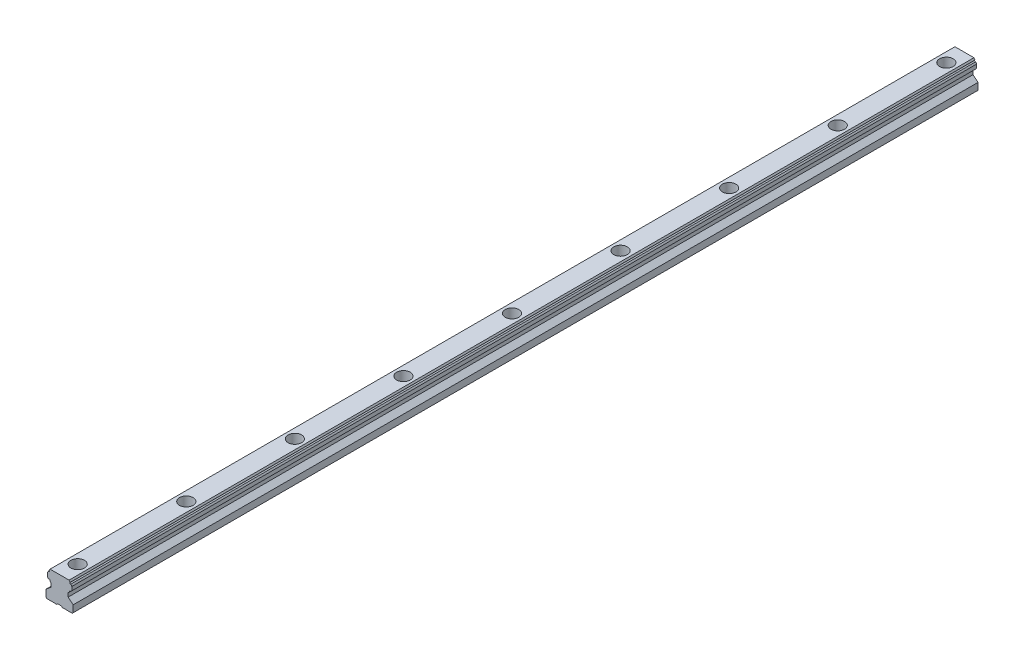
SolidWorks part; units mm, degrees
ref_plane "前视基准面" through (0, 0, 0) normal (0, 0, 1) x (1, 0, 0)
ref_plane "上视基准面" through (0, 0, 0) normal (0, 1, 0) x (1, 0, 0)
ref_plane "右视基准面" through (0, 0, 0) normal (1, 0, 0) x (0, 0, -1)
sketch "基准草图" plane through (0, 0, 0) normal (1, 0, 0) x (0, 0, -1)
  line L0 (0, 0) -> (60, 0) construction
  line L1 (0, 0) -> (0, 5)
  line L2 (60, 0) -> (80, 0) construction
  dimension "数量" = 5
  dimension "P" = 60
  dimension "E" = 20
sketch "草图1" plane through (0, 0, 0) normal (0, 0, 1) x (1, 0, 0)
  line L0 (0, 23.7) -> (0, 0) construction
  line L1 (-17, 21.7) -> (-17, 17.7)
  line L2 (17, 21.7) -> (17, 1)
  line L3 (-13, 23.7) -> (-13, 19.725) construction
  line L4 (-9.5, 23.7) -> (-9, 23.2)
  line L5 (-9, 23.2) -> (-3.3333, 23.2)
  line L6 (-3.3333, 23.2) -> (-2.8333, 23.7)
  line L7 (9.5, 23.7) -> (9, 23.2)
  line L8 (9, 23.2) -> (3.3333, 23.2)
  line L9 (3.3333, 23.2) -> (2.8333, 23.7)
  line L10 (-9.5, 23.7) -> (-15, 23.7)
  line L11 (15, 23.7) -> (9.5, 23.7)
  line L12 (-15, 23.7) -> (-17, 21.7)
  line L13 (2.8333, 23.7) -> (-2.8333, 23.7)
  line L14 (-16.2, 19.725) -> (16.2, 19.725)
  line L15 (-16.2, 19.725) -> (-16.5, 19.425)
  line L16 (-16.5, 19.425) -> (-16.5, 0.5)
  line L17 (-17, 17.7) -> (-16.5, 17.2) construction
  line L18 (-3.3333, 19.725) -> (-3.3333, 15.75)
  line L19 (3.3333, 19.725) -> (3.3333, 15.75)
  line L21 (-16, 0) -> (-7.5, 0)
  line L22 (-7.5, 0) -> (-4.75, 2.3075)
  line L23 (15, 23.7) -> (17, 21.7)
  line L24 (-4.75, 2.3075) -> (-4.75, 4.4182)
  line L25 (-4.75, 4.4182) -> (-5.4765, 5.0996)
  line L26 (-6.75, 6.294) -> (-6.75, 8.4047)
  line L27 (-6.75, 8.4047) -> (-6.2051, 9.2384)
  line L28 (-5.25, 10.7) -> (5.25, 10.7)
  line L29 (6.75, 8.4047) -> (6.2051, 9.2384)
  line L30 (6.75, 6.294) -> (6.75, 8.4047)
  line L31 (4.75, 4.4182) -> (5.4765, 5.0996)
  line L32 (4.75, 2.3075) -> (4.75, 4.4182)
  line L33 (7.5, 0) -> (4.75, 2.3075)
  line L34 (16, 0) -> (7.5, 0)
  line L35 (16.5, 19.425) -> (16.5, 0.5)
  line L36 (16.2, 19.725) -> (16.5, 19.425)
  line L37 (-7.5, 0) -> (-7.5, -3.8)
  line L38 (-7.5, -3.8) -> (-7, -4.3)
  line L39 (-7, -4.3) -> (-1.5, -4.3)
  line L40 (7.5, -3.8) -> (7, -4.3)
  line L41 (7.5, 0) -> (7.5, -3.8)
  line L42 (-1.5, -4.3) -> (-1, -3.8)
  line L43 (-1, -3.8) -> (1, -3.8)
  line L44 (1.5, -4.3) -> (1, -3.8)
  line L45 (1.5, -4.3) -> (7, -4.3)
  line L46 (-6.0235, 5.6126) -> (-6.75, 6.294)
  line L47 (-5.7949, 9.8662) -> (-5.25, 10.7)
  line L48 (5.7949, 9.8662) -> (5.25, 10.7)
  line L49 (6.0235, 5.6126) -> (6.75, 6.294)
  line L51 (8.2379, 3.1) -> (8.2379, 0.1) construction
  line L52 (6.7379, 1.6) -> (9.7379, 1.6) construction
  line L53 (8.0879, 2.9919) -> (8.0879, 1.75)
  line L54 (8.0879, 1.75) -> (6.846, 1.75)
  line L55 (8.3879, 1.75) -> (9.6299, 1.75)
  line L56 (8.3879, 2.9919) -> (8.3879, 1.75)
  line L57 (8.0879, 1.45) -> (6.846, 1.45)
  line L58 (8.3879, 1.45) -> (9.6299, 1.45)
  line L59 (8.3879, 0.2081) -> (8.3879, 1.45)
  line L60 (8.0879, 0.2081) -> (8.0879, 1.45)
  line L61 (-8.0879, 1.45) -> (-6.846, 1.45)
  line L62 (-8.0879, 0.2081) -> (-8.0879, 1.45)
  line L63 (-8.3879, 0.2081) -> (-8.3879, 1.45)
  line L64 (-8.3879, 1.45) -> (-9.6299, 1.45)
  line L65 (-8.3879, 1.75) -> (-9.6299, 1.75)
  line L66 (-8.0879, 1.75) -> (-6.846, 1.75)
  line L67 (-8.0879, 2.9919) -> (-8.0879, 1.75)
  line L68 (-8.3879, 2.9919) -> (-8.3879, 1.75)
  line L69 (-2.8333, 20.225) -> (2.8333, 20.225)
  line L70 (-3.3333, 19.725) -> (-2.8333, 20.225)
  line L71 (-16.75, 17.45) -> (-16.75, 0.75)
  line L72 (3.3333, 19.725) -> (2.8333, 20.225)
  line L73 (-16.75, 17.45) -> (-17, 17.7)
  line L74 (-16, 0) -> (-16.75, 0.75)
  line L75 (16, 0) -> (17, 1)
  arc A0 (-3.3333, 15.75) -> (3.3333, 15.75) centre (0, 15.75) ccw
  arc A1 (-6.2051, 9.2384) -> (-5.7949, 9.8662) centre (-6, 9.5523) ccw
  arc A2 (-5.4765, 5.0996) -> (-6.0235, 5.6126) centre (-5.75, 5.3561) ccw
  arc A3 (5.4765, 5.0996) -> (6.0235, 5.6126) centre (5.75, 5.3561) cw
  arc A4 (6.2051, 9.2384) -> (5.7949, 9.8662) centre (6, 9.5523) cw
  circle A5 centre (8.2379, 1.6) radius 1.5
  circle A6 centre (-8.2379, 1.6) radius 1.5
  circle A7 centre (8.2379, 1.6) radius 1.4
  circle A8 centre (-8.2379, 1.6) radius 1.4
  point P4 (-13, 23.7)
  point P6 (13, 23.7)
  point P11 (-9.5, 23.7)
  point P12 (-2.8333, 23.7)
  point P13 (9.5, 23.7)
  point P14 (2.8333, 23.7)
  point P55 (-7.5, 0)
  point P60 (0, 12.4167)
  dimension "D18" = 0.75
  dimension "D19" = 0.75
  dimension "D20" = 3
  dimension "D21" = 1.7
  dimension "D24" = 0.1
  dimension "D25" = 1.6
  dimension "D1" = 2
  dimension "D2" = 45
  dimension "W" = 34
  dimension "D3" = 45
  dimension "B1" = 4
  dimension "B" = 26
  dimension "T" = 6
  dimension "H" = 28
  dimension "D4" = 45
  dimension "D5" = 0.5
  dimension "D6" = 6.6667
  dimension "D7" = 45
  dimension "D8" = 0.5
  dimension "D9" = 0.5
  dimension "H2" = 7.95
  dimension "D10" = 3.975
  dimension "D11" = 45
  dimension "Wr" = 15
  dimension "D12" = 2
  dimension "N" = 9.5
  dimension "D13" = 45
  dimension "D14" = 9.5
  dimension "H1" = 4.3
  dimension "D15" = 0.3
  dimension "D16" = 10.5
  dimension "D17" = 0.3
  dimension "D22" = 0.3
  dimension "D23" = 0.3
  dimension "D26" = 0.5
  dimension "D27" = 45
  dimension "Hr" = 15
  dimension "D28" = 1.5
  dimension "D29" = 100
  dimension "D30" = 40
  dimension "D31" = 1
  dimension "D32" = 1
  dimension "D33" = 45
extrude "凸台-拉伸2" add sketch "草图1" along normal mid plane 500 contours L29 A4 L48 L28 L47 A1 L27 L26 L46 A2 L25 L24 L22 L37 L38 L39 L42 L43 L44 L45 L40 L41 L33 L32 L31 A3 L49 L30
sketch "草图4" plane through (0, 10.7, 0) normal (0, 1, 0) x (1, 0, 0)
  line L0 (-5.25, -250) -> (5.25, -250) construction
  circle A0 centre (0, -240) radius 2.25
  point P5 (0, -250)
  dimension "D1" = 4.5
  dimension "D2" = 10
extrude "切除-拉伸2" cut sketch "草图4" against normal through all
sketch "草图5" plane through (0, 10.7, 0) normal (0, 1, 0) x (1, 0, 0)
  circle A0 centre (0, -240) radius 3.75
  dimension "D1" = 7.5
extrude "切除-拉伸3" cut sketch "草图5" against normal blind 5.3
pattern_linear "阵列(线性)1" count 9 spacing 60 along (0, 0, -1) of "切除-拉伸2", "切除-拉伸3"
